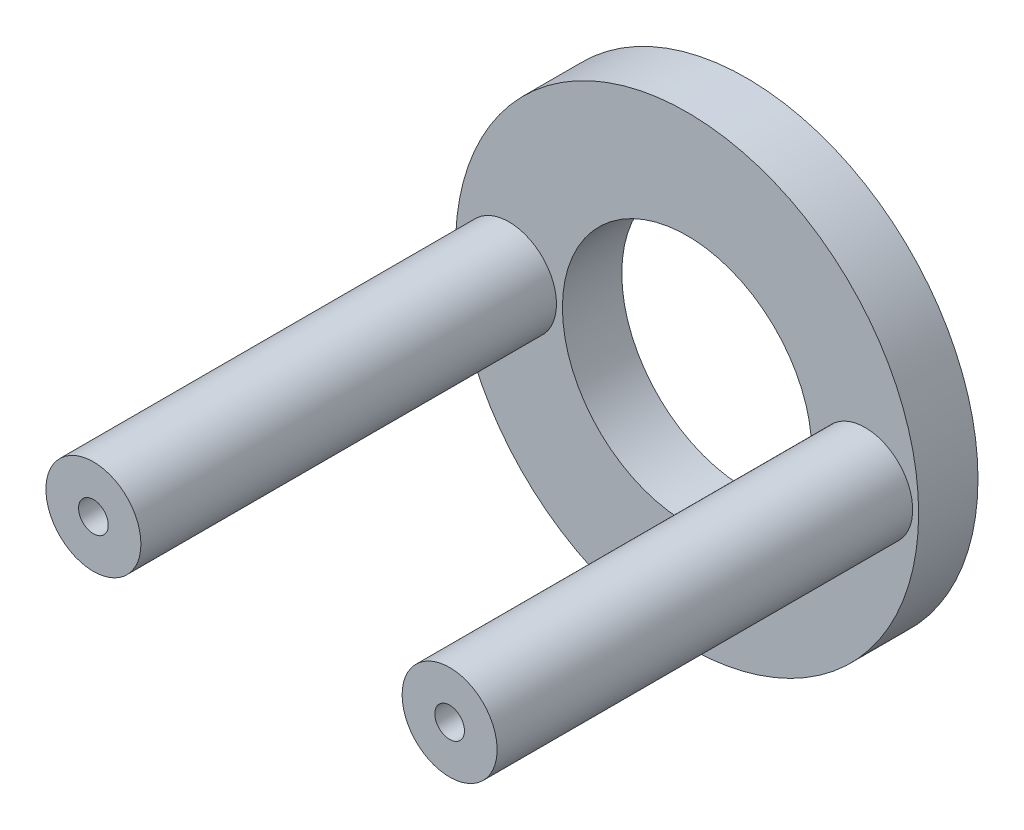
SolidWorks part; units mm, degrees
ref_plane "Front Plane" through (0, 0, 0) normal (0, 0, 1) x (1, 0, 0)
ref_plane "Top Plane" through (0, 0, 0) normal (0, 1, 0) x (1, 0, 0)
ref_plane "Right Plane" through (0, 0, 0) normal (1, 0, 0) x (0, 0, -1)
sketch "Sketch1" plane through (0, 0, 0) normal (0, 0, 1) x (1, 0, 0)
  circle A0 centre (0, 0) radius 10.5
  circle A1 centre (0, 0) radius 19.5
  circle A2 centre (0, 0) radius 15 construction
  dimension "D1" = 30
  dimension "D2" = 21
  dimension "D3" = 39
extrude "Boss-Extrude1" add sketch "Sketch1" along normal blind 5
sketch "Sketch3" plane through (0, 0, 5) normal (0, 0, 1) x (1, 0, 0)
  line L0 (19.5, 0) -> (-19.5, 0) construction
  line L1 (0, -19.5) -> (0, 19.5) construction
  circle A0 centre (0, 0) radius 19.5 construction
  circle A1 centre (-15, 0) radius 4
  circle A2 centre (15, 0) radius 4
  circle A3 centre (0, 0) radius 10.5 construction
  dimension "D1" = 8
  dimension "D2" = 0.5
extrude "Boss-Extrude2" add sketch "Sketch3" along normal blind 35
sketch "Sketch4" plane through (0, 0, 40) normal (0, 0, 1) x (1, 0, 0)
  circle A0 centre (15, 0) radius 1.25
  circle A1 centre (-15, 0) radius 1.25
  dimension "D1" = 2.5
  dimension "D2" = 2.5
extrude "Cut-Extrude1" cut sketch "Sketch4" against normal blind 7
